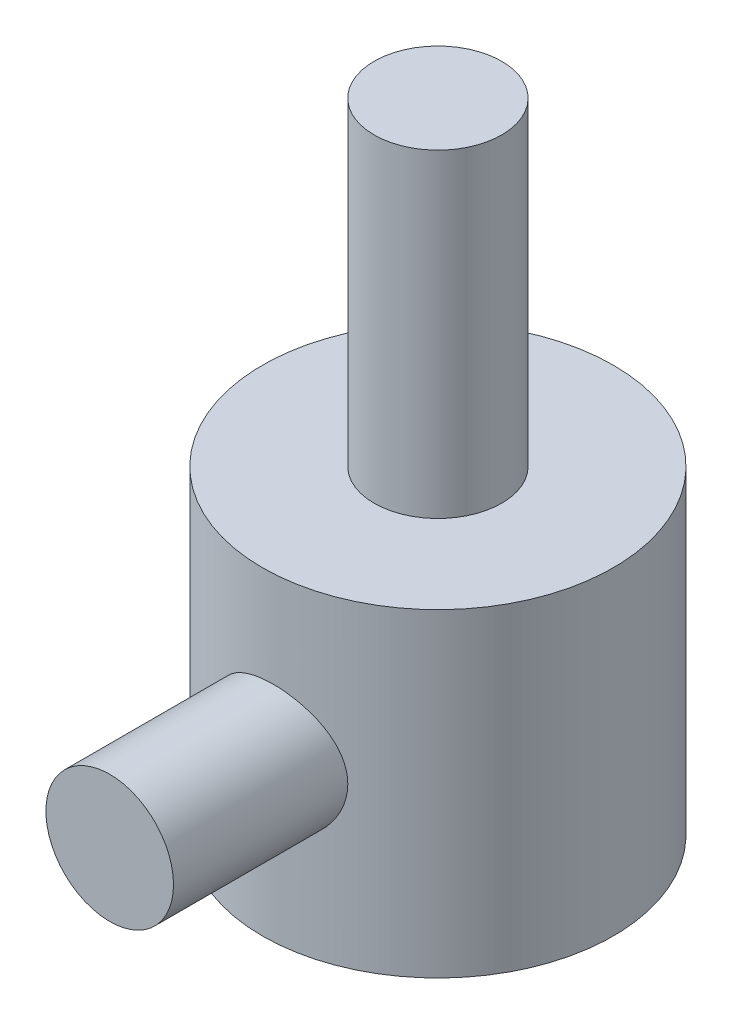
SolidWorks part; units mm, degrees
ref_plane "Front Plane" through (0, 0, 0) normal (0, 0, 1) x (1, 0, 0)
ref_plane "Top Plane" through (0, 0, 0) normal (0, 1, 0) x (1, 0, 0)
ref_plane "Right Plane" through (0, 0, 0) normal (1, 0, 0) x (0, 0, -1)
sketch "Sketch1" plane through (0, 0, 0) normal (0, 1, 0) x (1, 0, 0)
  circle A0 centre (0, 0) radius 55
extrude "Boss-Extrude1" add sketch "Sketch1" along normal blind 100
sketch "Sketch2" plane through (0, 100, 0) normal (0, 1, 0) x (1, 0, 0)
  circle A0 centre (0, 0) radius 20
extrude "Boss-Extrude2" add sketch "Sketch2" along normal blind 100
ref_plane "Plane1" through (0, 0, 55) normal (0, 0, 1) x (1, 0, 0)
sketch "Sketch3" plane through (0, 0, 55) normal (0, 0, 1) x (1, 0, 0)
  circle A0 centre (2.1157, 50) radius 20
  dimension "D1" = 50
extrude "Boss-Extrude3" add sketch "Sketch3" along normal blind 50 and the other way blind 20
